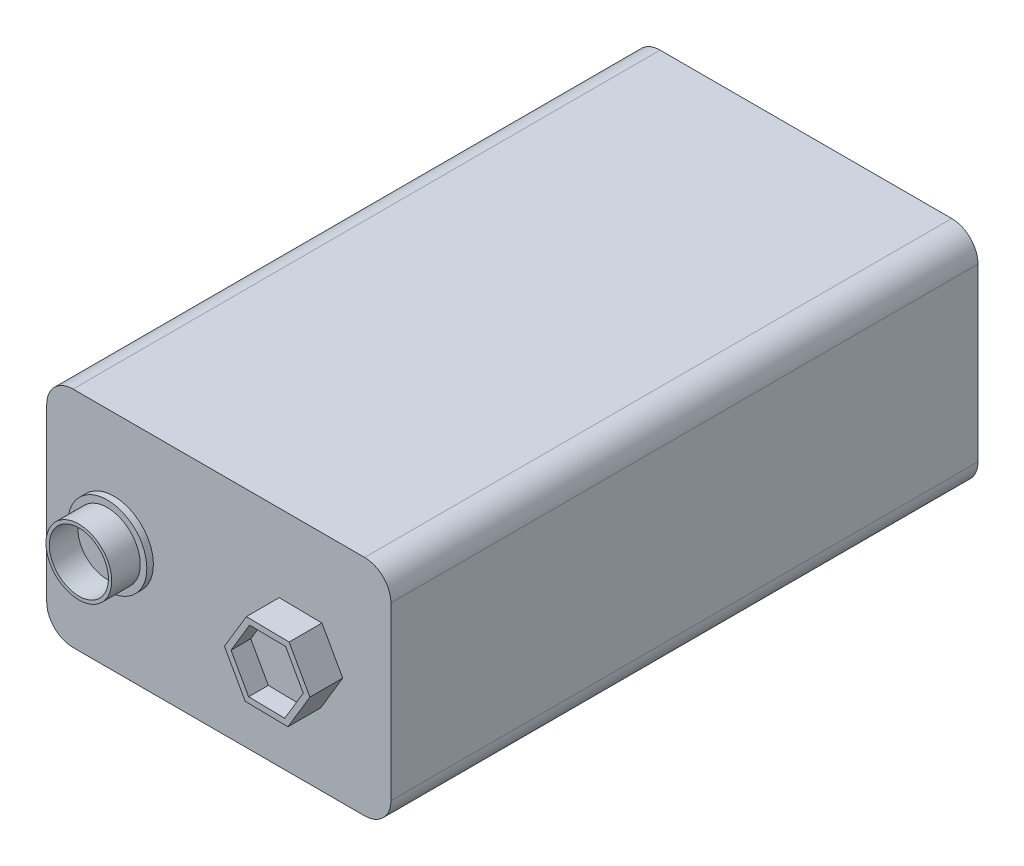
SolidWorks part; units mm, degrees
ref_plane "Front Plane" through (0, 0, 0) normal (0, 0, 1) x (1, 0, 0)
ref_plane "Top Plane" through (0, 0, 0) normal (0, 1, 0) x (1, 0, 0)
ref_plane "Right Plane" through (0, 0, 0) normal (1, 0, 0) x (0, 0, -1)
sketch "Sketch2" plane through (0, 0, 0) normal (0, 0, 1) x (1, 0, 0)
  line L1 (-10.9173, 9.3798) -> (11.2727, 9.3798)
  line L2 (-12.9173, 7.3798) -> (-12.9173, -5.6502)
  line L3 (-10.9173, -7.6502) -> (11.2727, -7.6502)
  line L4 (13.2727, 7.3798) -> (13.2727, -5.6502)
  arc A0 (11.2727, -7.6502) -> (13.2727, -5.6502) centre (11.2727, -5.6502) ccw
  arc A1 (-12.9173, -5.6502) -> (-10.9173, -7.6502) centre (-10.9173, -5.6502) ccw
  arc A2 (13.2727, 7.3798) -> (11.2727, 9.3798) centre (11.2727, 7.3798) ccw
  arc A3 (-10.9173, 9.3798) -> (-12.9173, 7.3798) centre (-10.9173, 7.3798) ccw
  point P8 (-12.9173, -7.6502)
  point P11 (13.2727, 9.3798)
  point P14 (-12.9173, 9.3798)
  dimension "D3" = 2
  dimension "D1" = 17.03
  dimension "D2" = 26.19
extrude "Boss-Extrude1" add sketch "Sketch2" along normal blind 44.67
sketch "Sketch5" plane through (0, 0, 44.67) normal (0, 0, 1) x (1, 0, 0)
  circle A0 centre (-7.8024, 0.8794) radius 2.25
  circle A1 centre (-7.8024, 0.8794) radius 2.5
  dimension "D1" = 4.5
  dimension "D2" = 5
extrude "Boss-Extrude3" add sketch "Sketch5" along normal blind 2.67
sketch "Sketch6" plane through (0, 0, 44.67) normal (0, 0, 1) x (1, 0, 0)
  line L1 (7.9369, -2.196) -> (9.6061, 0.5931)
  line L2 (9.6061, 0.5931) -> (8.0253, 3.4332)
  line L3 (8.0253, 3.4332) -> (4.7753, 3.4842)
  line L4 (4.7753, 3.4842) -> (3.1061, 0.6951)
  line L5 (3.1061, 0.6951) -> (4.6869, -2.145)
  line L6 (4.6869, -2.145) -> (7.9369, -2.196)
  circle A0 centre (6.3561, 0.6441) radius 2.8149 construction
  dimension "D1" = 3.25
extrude "Boss-Extrude4" add sketch "Sketch6" along normal blind 2.5
sketch "Sketch7" plane through (0, 0, 47.17) normal (0, 0, 1) x (1, 0, 0)
  line L0 (3.1061, 0.6951) -> (9.6061, 0.5931) construction
  line L1 (6.3561, 0.6441) -> (6.4003, 3.4587) construction
  line L2 (8.0253, 3.4332) -> (4.7753, 3.4842) construction
  line L4 (4.9441, -1.7151) -> (7.6932, -1.7583)
  line L5 (7.6932, -1.7583) -> (9.1052, 0.6009)
  line L6 (9.1052, 0.6009) -> (7.7681, 3.0033)
  line L7 (7.7681, 3.0033) -> (5.019, 3.0465)
  line L8 (5.019, 3.0465) -> (3.607, 0.6873)
  line L9 (3.607, 0.6873) -> (4.9441, -1.7151)
  circle A0 centre (6.3561, 0.6441) radius 2.3811 construction
  dimension "D1" = 2.7494
extrude "Cut-Extrude1" cut sketch "Sketch7" against normal blind 1.5
sketch "Sketch8" plane through (0, 0, 44.67) normal (0, 0, 1) x (1, 0, 0)
  line L0 (-10.0524, 0.8794) -> (-5.5524, 0.8794) construction
  line L1 (-7.8024, 3.1294) -> (-7.8024, -1.3706) construction
  circle A0 centre (-7.8024, 0.8794) radius 2.25 construction
  circle A1 centre (-7.8024, 0.8794) radius 2.25 construction
  circle A2 centre (-7.8024, 0.8794) radius 3
  dimension "D1" = 6
extrude "Boss-Extrude5" add sketch "Sketch8" along normal blind 0.5
sketch "Sketch10" plane through (0, -7.6502, 0) normal (0, -1, 0) x (1, 0, 0)
  line L0 (0, 0) -> (0.1777, 44.67) construction
  line L1 (-10.9173, 44.67) -> (11.2727, 44.67) construction
  text T0 "DURACELL"
extrude "Cut-Extrude2" cut sketch "Sketch10" against normal blind 0.5
